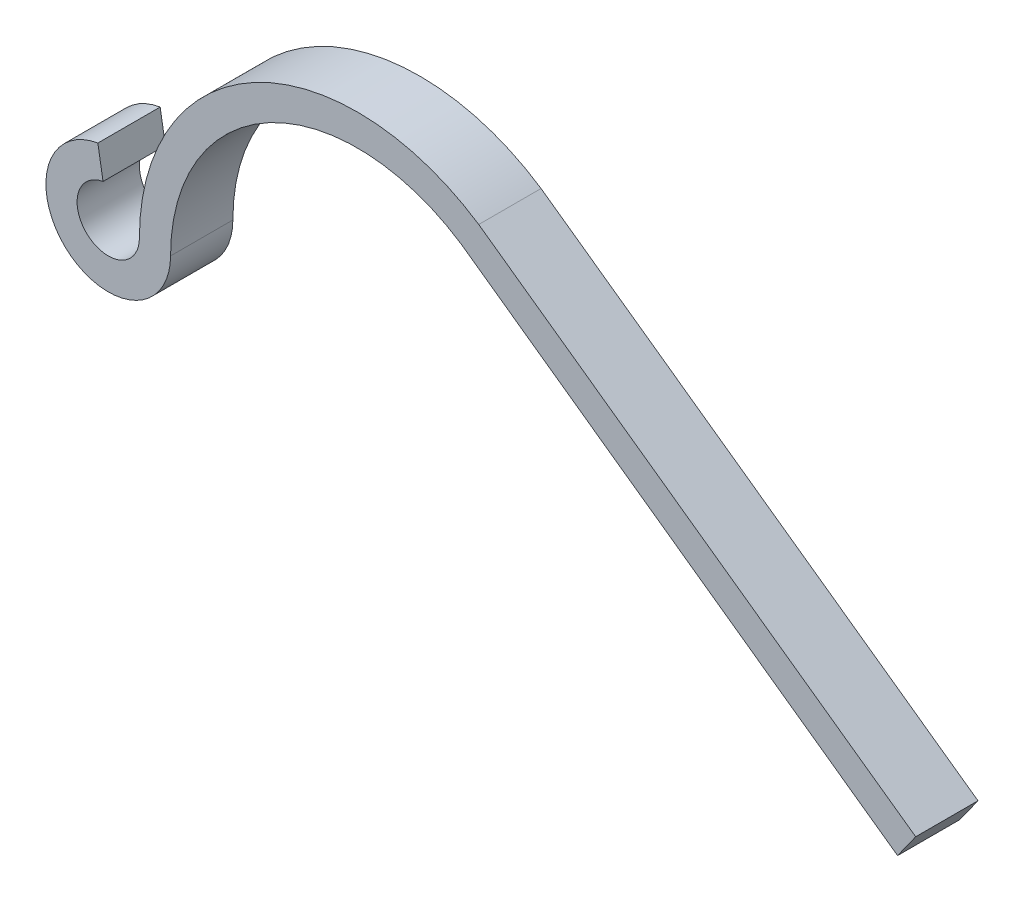
SolidWorks part; units mm, degrees
ref_plane "Plane1" through (0, 0, 0) normal (0, 0, 1) x (1, 0, 0)
ref_plane "Plane2" through (0, 0, 0) normal (0, 1, 0) x (1, 0, 0)
ref_plane "Plane3" through (0, 0, 0) normal (1, 0, 0) x (0, 0, -1)
other "Configuration Table"
sketch "Sketch1" plane through (0, 0, 0) normal (0, 0, 1) x (1, 0, 0)
  line L0 (89.5673, -20.9298) -> (19.4521, 29.0967)
  line L1 (-40.8333, 4.9301) -> (-41.6667, 9.8601)
  line L2 (86.6632, -25) -> (89.5673, -20.9298)
  line L6 (86.6632, -25) -> (16.6123, 24.9806)
  arc A0 (-35, 0) -> (-40.8333, 4.9301) centre (-40, 0) cw
  arc A1 (-35, 0) -> (19.4521, 29.0967) centre (0, 0) cw
  arc A2 (-30, 0) -> (-41.6667, 9.8601) centre (-40, 0) cw
  arc A6 (-30, 0) -> (16.6123, 24.9806) centre (0, 0) cw
  dimension "D1" = 5
extrude "Base-Extrude" add sketch "Sketch1" along normal blind 10
